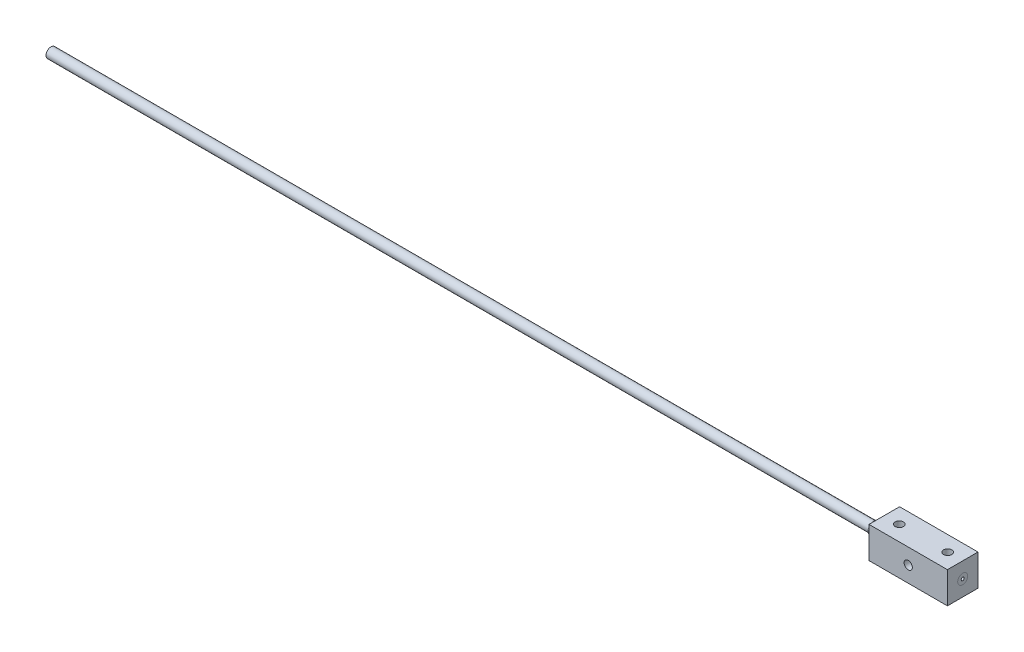
SolidWorks part; units mm, degrees
ref_plane "Спереди" through (0, 0, 0) normal (0, 0, 1) x (1, 0, 0)
ref_plane "Сверху" through (0, 0, 0) normal (0, 1, 0) x (1, 0, 0)
ref_plane "Справа" through (0, 0, 0) normal (1, 0, 0) x (0, 0, -1)
sketch "Эскиз1" plane through (0, 0, 0) normal (0, 1, 0) x (1, 0, 0)
  line L1 (-20, 7.8) -> (20, 7.8)
  line L2 (-20, 7.8) -> (-20, -7.8)
  line L3 (-20, -7.8) -> (20, -7.8)
  line L4 (20, 7.8) -> (20, -7.8)
  line L5 (-20, 7.8) -> (20, -7.8) construction
  line L6 (-20, -7.8) -> (20, 7.8) construction
  point P0 (0, 0)
  dimension "D1" = 15.6
  dimension "D2" = 40
extrude "Бобышка-Вытянуть1" add sketch "Эскиз1" along normal blind 16 contours L2 L3 L4 L1
sketch "Эскиз2" plane through (0, 16, 0) normal (0, 1, 0) x (1, 0, 0)
  line L0 (0, 0) -> (0, 17.2211) construction
  circle A0 centre (-12.3375, 0) radius 2.1
  circle A1 centre (12.3375, 0) radius 2.1
  dimension "D1" = 4.2
extrude "Вырез-Вытянуть1" cut sketch "Эскиз2" against normal through all
sketch "Эскиз3" plane through (-20, 0, 0) normal (-1, 0, 0) x (0, 0, 1)
  line L1 (-7.8, 16) -> (7.8, 16) construction
  line L2 (-7.8, 16) -> (-7.8, 0) construction
  line L3 (-7.8, 0) -> (7.8, 0) construction
  line L4 (7.8, 16) -> (7.8, 0) construction
  line L5 (-7.8, 16) -> (7.8, 0) construction
  line L6 (-7.8, 0) -> (7.8, 16) construction
  circle A0 centre (0, 8) radius 2.55
  point P0 (0, 8)
  dimension "D1" = 5.1
extrude "Вырез-Вытянуть2" cut sketch "Эскиз3" against normal through all
sketch "Эскиз4" plane through (20, 0, 0) normal (1, 0, 0) x (0, 0, -1)
  circle A0 centre (0, 8) radius 2.55 construction
  circle A1 centre (0, 8) radius 2.55
  circle A2 centre (0, 8) radius 0.7696
extrude "Бобышка-Вытянуть2" add sketch "Эскиз4" against normal blind 465 separate body
sketch "Эскиз5" plane through (-20, 0, 0) normal (-1, 0, 0) x (0, 0, 1)
  circle A0 centre (0, 8) radius 2.55 construction
  circle A1 centre (0, 8) radius 2.55
  circle A2 centre (0, 8) radius 3
  dimension "D1" = 6
extrude "Бобышка-Вытянуть3" add sketch "Эскиз5" along normal blind 5.3
sketch "Эскиз6" plane through (-25.3, 0, 0) normal (-1, 0, 0) x (0, 0, 1)
  circle A0 centre (0, 8) radius 3.7
  circle A1 centre (0, 8) radius 3
  circle A2 centre (0, 8) radius 3
  dimension "D2" = 0.7
  dimension "D1" = 0
extrude "Вырез-Вытянуть3" cut sketch "Эскиз6" against normal blind 8
ref_plane "Плоскость1" through (0, 8, 0) normal (0, 1, 0) x (1, 0, 0)
sketch "Эскиз7" plane through (0, 16, 0) normal (0, 1, 0) x (1, 0, 0)
  circle A0 centre (12.3375, 0) radius 2.1 construction
  circle A1 centre (-12.3375, 0) radius 2.1 construction
  circle A2 centre (12.3375, 0) radius 2.1
  circle A3 centre (-12.3375, 0) radius 2.1
  circle A4 centre (-12.3375, 0) radius 1.5
  circle A5 centre (12.3375, 0) radius 1.5
  dimension "D1" = 3
extrude "Бобышка-Вытянуть4" [suppressed] add sketch "Эскиз7" against normal blind 4 separate body
mirror "Зеркальное отражение3" [suppressed] about plane through (0, 8, 0) normal (0, 1, 0)
ref_plane "Плоскость2" through (-445, 0, 0) normal (-1, 0, 0) x (0, 0, 1)
sketch "Эскиз8" plane through (0, 0, -7.8) normal (0, 0, -1) x (-1, 0, 0)
  line L0 (8.58, 8) -> (-8.58, 8) construction
  line L1 (-20, 0) -> (20, 16) construction
  circle A0 centre (0, 8) radius 2.1
  point P5 (0, 8)
  dimension "D1" = 4.2
extrude "Вырез-Вытянуть4" cut sketch "Эскиз8" against normal through all
